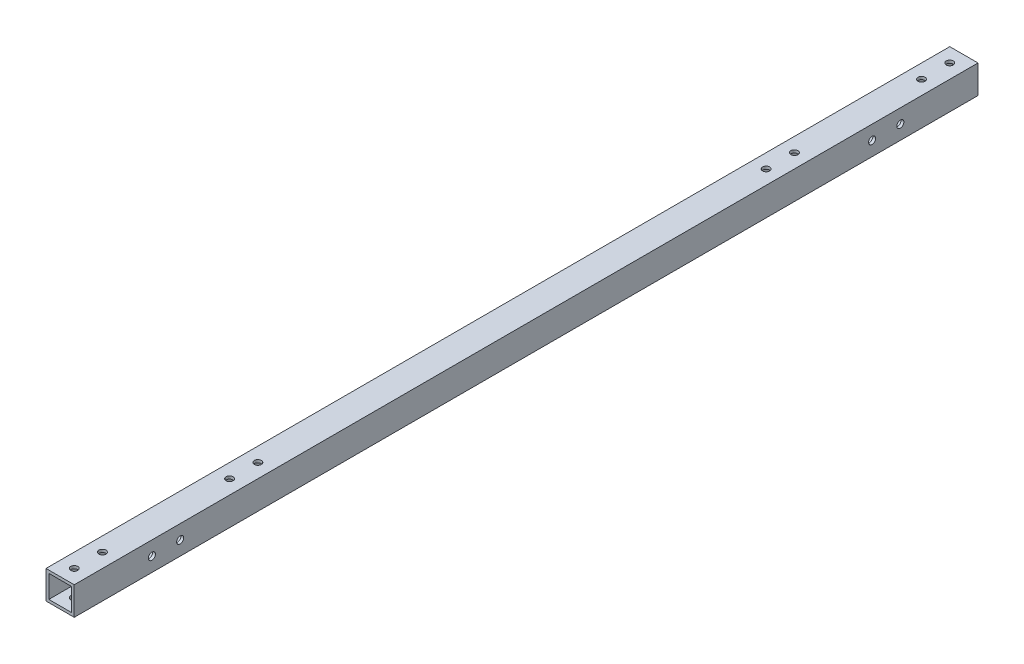
SolidWorks part; units mm, degrees
material "1345 Alloy"
ref_plane "Front Plane" through (0, 0, 0) normal (0, 0, 1) x (1, 0, 0)
ref_plane "Top Plane" through (0, 0, 0) normal (0, 1, 0) x (1, 0, 0)
ref_plane "Right Plane" through (0, 0, 0) normal (1, 0, 0) x (0, 0, -1)
sketch "Sketch1" plane through (0, 0, 0) normal (0, 0, 1) x (1, 0, 0)
  line L1 (-10, 10) -> (10, 10)
  line L2 (-10, 10) -> (-10, -10)
  line L3 (-10, -10) -> (10, -10)
  line L4 (10, 10) -> (10, -10)
  line L5 (-10, 10) -> (10, -10) construction
  line L6 (-10, -10) -> (10, 10) construction
  line L7 (-8, 8) -> (8, 8)
  line L8 (-8, 8) -> (-8, -8)
  line L9 (-8, -8) -> (8, -8)
  line L10 (8, 8) -> (8, -8)
  line L11 (-8, 8) -> (8, -8) construction
  line L12 (-8, -8) -> (8, 8) construction
  point P0 (0, 0)
  point P6 (0, 0)
  dimension "D1" = 20
  dimension "D2" = 20
  dimension "D3" = 16
  dimension "D4" = 16
extrude "Boss-Extrude1" add sketch "Sketch1" along normal blind 640
sketch "Sketch2" plane through (0, 10, 0) normal (0, 1, 0) x (1, 0, 0)
  line L0 (0, 63.7853) -> (0, -702.9573) construction
  line L1 (10, 0) -> (-10, 0) construction
  line L2 (-10, -320) -> (77.7281, -320) construction
  line L3 (-10, -640) -> (-10, 0) construction
  circle A0 centre (0, -10) radius 2.5
  circle A1 centre (0, -630) radius 2.5
  circle A2 centre (0, -30) radius 2.5
  circle A3 centre (0, -610) radius 2.5
  dimension "D1" = 5
  dimension "D3" = 5
  dimension "D2" = 10
  dimension "D4" = 20
extrude "Cut-Extrude1" cut sketch "Sketch2" against normal through all
sketch "Sketch3" plane through (0, 10, 0) normal (0, 1, 0) x (1, 0, 0)
  line L0 (0, 27.5941) -> (0, -663.2953) construction
  line L1 (10, 0) -> (-10, 0) construction
  line L2 (-10, -320) -> (-145.1363, -320) construction
  line L3 (-10, -640) -> (-10, 0) construction
  circle A0 centre (0, -140) radius 2.5
  circle A1 centre (0, -500) radius 2.5
  circle A2 centre (0, -120) radius 2.5
  circle A3 centre (0, -520) radius 2.5
  dimension "D1" = 5
  dimension "D3" = 5
  dimension "D2" = 140
  dimension "D4" = 20
extrude "Cut-Extrude2" cut sketch "Sketch3" against normal through all
sketch "Sketch4" plane through (-10, 0, 0) normal (-1, 0, 0) x (0, 0, 1)
  line L0 (-37.683, 0) -> (665.2418, 0) construction
  line L1 (320, 10) -> (320, -10) construction
  line L2 (640, 10) -> (0, 10) construction
  line L3 (640, -10) -> (0, -10) construction
  line L4 (65, 10) -> (65, -10) construction
  line L5 (0, 10) -> (0, -10) construction
  circle A0 centre (55, 0) radius 2.5
  circle A1 centre (75, 0) radius 2.5
  circle A2 centre (565, 0) radius 2.5
  circle A3 centre (585, 0) radius 2.5
  dimension "D2" = 5
  dimension "D1" = 65
  dimension "D3" = 10
extrude "Cut-Extrude3" cut sketch "Sketch4" against normal through all
